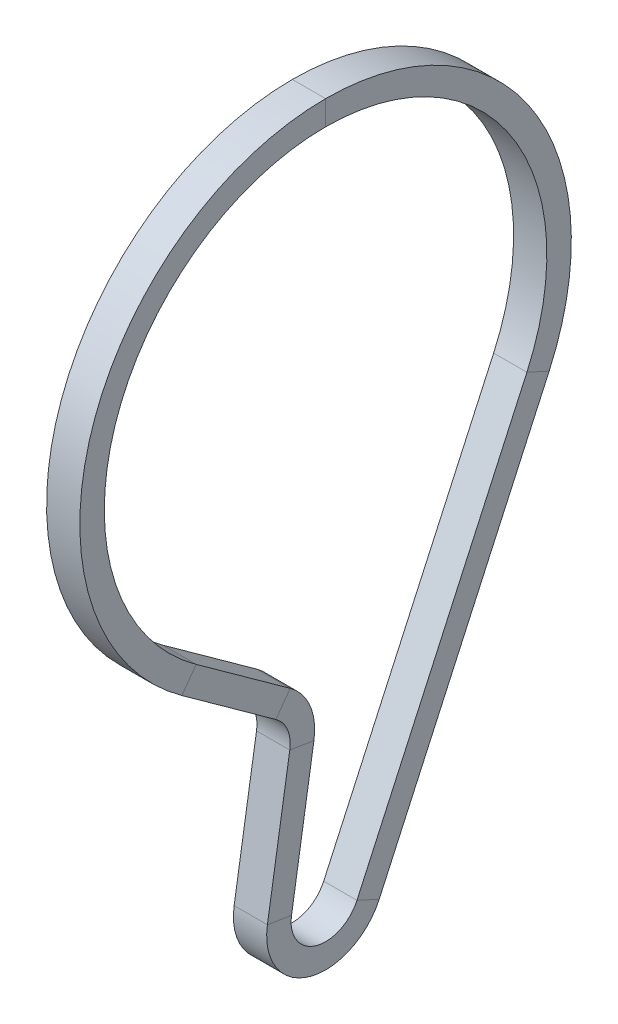
SolidWorks part; units mm, degrees
material "6061-T6 (SS)"
ref_plane "Front Plane" through (0, 0, 0) normal (0, 0, 1) x (1, 0, 0)
ref_plane "Top Plane" through (0, 0, 0) normal (0, 1, 0) x (1, 0, 0)
ref_plane "Right Plane" through (0, 0, 0) normal (1, 0, 0) x (0, 0, -1)
sketch "Sketch1" plane through (0, 0, 0) normal (1, 0, 0) x (0, 0, -1)
  line L0 (16.5494, -182.8128) -> (82.7469, -37.7642)
  line L1 (-17.9637, -172.3908) -> (-9.2454, -117.8055)
  line L2 (-16.5717, -100.1793) -> (-53.1871, -73.7856)
  line L3 (0, 0) -> (0, -175.26) construction
  line L4 (0, -106.68) -> (-89.2045, -133.7484) construction
  arc A0 (82.7469, -37.7642) -> (-53.1871, -73.7856) centre (0, 0) ccw
  arc A2 (-17.9637, -172.3908) -> (16.5494, -182.8128) centre (0, -175.26) ccw
  arc A3 (-9.2454, -117.8055) -> (-16.5717, -100.1793) centre (-27.2091, -114.9364) ccw
  circle A4 centre (0, 0) radius 90.957 construction
  circle A5 centre (0, -175.26) radius 18.1914 construction
  dimension "D1" = 181.9141
  dimension "D2" = 36.3828
  dimension "D4" = 175.26
  dimension "D5" = 73.12
  dimension "D6" = 68.58
sketch "Sketch2" plane through (0, 0, 0) normal (0, 0, 1) x (1, 0, 0)
  line L1 (-6.477, 95.7195) -> (6.477, 95.7195)
  line L2 (-6.477, 95.7195) -> (-6.477, 86.1945)
  line L3 (-6.477, 86.1945) -> (6.477, 86.1945)
  line L4 (6.477, 95.7195) -> (6.477, 86.1945)
  line L5 (-6.477, 95.7195) -> (6.477, 86.1945) construction
  line L6 (-6.477, 86.1945) -> (6.477, 95.7195) construction
  point P0 (0, 90.957)
  dimension "D1" = 12.954
  dimension "D2" = 9.525
sweep "Sweep1" add profiles "Sketch2" path "Sketch1"
sketch "Chain Removal Sketch" plane through (0, 0, 0) normal (1, 0, 0) x (0, 0, -1)
  line L0 (84.5341, -33.5732) -> (24.4119, -184.9553)
  line L1 (-24.4119, -184.9553) -> (-84.5341, -33.5732)
  line L2 (28.8381, -186.7132) -> (19.9857, -183.1974) construction
  line L3 (12.2168, -180.8355) -> (20.882, -184.7902) construction
  arc A0 (84.5341, -33.5732) -> (-84.5341, -33.5732) centre (0, 0) ccw
  arc A1 (24.4119, -184.9553) -> (-24.4119, -184.9553) centre (0, -175.26) cw
  arc A2 (-17.9637, -172.3908) -> (16.5494, -182.8128) centre (0, -175.26) ccw construction
  arc A3 (82.7469, -37.7642) -> (-53.1871, -73.7856) centre (0, 0) ccw construction
  circle A4 centre (0, -175.26) radius 20.6375
sketch "Sketch3" plane through (6.477, 0, 0) normal (1, 0, 0) x (0, 0, -1)
  line L0 (0, -206.9465) -> (0, -197.4215) construction
  line L1 (12.2168, -180.8355) -> (20.882, -184.7902) construction
  circle A0 centre (0, -175.26) radius 31.6865
  circle A1 centre (0, -175.26) radius 22.1615
  circle A3 centre (0, -175.26) radius 20.6375 construction
  dimension "D1" = 1.524
extrude "Boss-Extrude1" [suppressed] add sketch "Sketch3" against normal up to vertex separate body
sketch "Sketch4" plane through (6.477, 0, 0) normal (1, 0, 0) x (0, 0, -1)
  line L0 (-10.3024, 7.4263) -> (0, 0) construction
  line L1 (2.0031, 12.541) -> (0, 0) construction
  line L2 (-22.6666, -171.6397) -> (-13.9483, -117.0544) construction
  line L3 (-19.3565, -104.0427) -> (-55.972, -77.649) construction
  line L4 (2.0031, 12.541) -> (-10.3024, 7.4263) construction
  dimension "D1" = 12.7
  dimension "D2" = 13.3261
sketch "Sketch5" plane through (0, 0, 0) normal (1, 0, 0) x (0, 0, -1)
  line L0 (16.5494, -182.8128) -> (82.7469, -37.7642) construction
  line L1 (16.5494, -182.8128) -> (82.7469, -37.7642)
  line L2 (-17.4843, -170.2373) -> (-2.4026, -117.7372)
  line L4 (0, -106.68) -> (-89.2045, -133.7484) construction
  line L6 (-11.4808, -96.5818) -> (-42.0305, -80.6637)
  line L8 (0, 0) -> (8.8142, 0) construction
  arc A0 (82.7469, -37.7642) -> (-53.1871, -73.7856) centre (0, 0) ccw construction
  arc A1 (82.7469, -37.7642) -> (-42.0305, -80.6637) centre (0, 0) ccw
  arc A3 (-17.9637, -172.3908) -> (16.5494, -182.8128) centre (0, -175.26) ccw construction
  arc A4 (-17.4843, -170.2373) -> (16.5494, -182.8128) centre (0, -175.26) ccw
  circle A5 centre (0, -175.26) radius 18.1914 construction
  arc A6 (-2.4026, -117.7372) -> (-11.4808, -96.5818) centre (-19.8869, -112.7145) ccw
  arc A8 (-9.2454, -117.8055) -> (-16.5717, -100.1793) centre (-27.2091, -114.9364) ccw construction
  dimension "D1" = 7.6518
  dimension "D3" = 8.8142
equation "\"D1@Sketch1\"=.375*60/pi"
equation "\"D2@Sketch1\"=12*.375/pi"
equation "\"D1@Chain Removal Sketch\" = \"D3@Sketch1\""
equation "\"D3@Sketch5\"=\"D2@Sketch5\"-\"d3@sketch1\""
